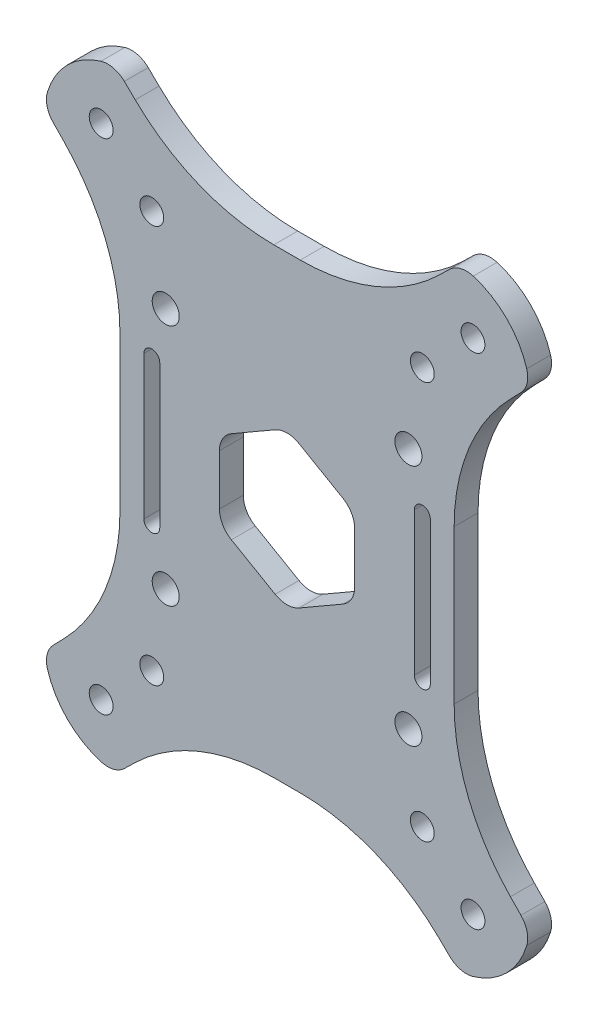
SolidWorks part; units mm, degrees
ref_plane "Draufsicht" through (0, 0, 0) normal (0, 0, 1) x (1, 0, 0)
ref_plane "Seitenansicht" through (0, 0, 0) normal (0, 1, 0) x (1, 0, 0)
ref_plane "Vorderansicht" through (0, 0, 0) normal (1, 0, 0) x (0, 0, -1)
sketch "Skizze1" plane through (0, 0, 0) normal (0, 0, 1) x (1, 0, 0)
  line L0 (-15.25, 15.25) -> (15.25, -15.25) construction
  line L1 (-15.25, 15.25) -> (15.25, 15.25) construction
  line L2 (-15.25, 15.25) -> (-15.25, -15.25) construction
  line L3 (-15.25, -15.25) -> (15.25, -15.25) construction
  line L4 (15.25, 15.25) -> (15.25, -15.25) construction
  line L5 (-17, 25) -> (17, 25) construction
  line L6 (-17, 25) -> (-17, -25) construction
  line L7 (-17, -25) -> (17, -25) construction
  line L9 (15.25, 15.25) -> (-15.25, -15.25) construction
  line L10 (-17, 25) -> (17, -25) construction
  line L11 (17, -25) -> (17, 25) construction
  line L12 (17, 25) -> (-17, -25) construction
  line L13 (17, 25) -> (23.364, 31.364) construction
  line L14 (-23.364, 31.364) -> (-17, 25) construction
  line L16 (-23.364, -31.364) -> (-17, -25) construction
  line L18 (23.364, -31.364) -> (17, -25) construction
  dimension "D1" = 30.5
  dimension "D2" = 30.5
  dimension "D3" = 50
  dimension "D4" = 34
  dimension "D5" = 135
  dimension "D6" = 9
sketch "Skizze2" plane through (0, 0, 0) normal (0, 0, 1) x (1, 0, 0)
  line L0 (-21, -19.8076) -> (-21, 19.8076)
  line L1 (-21, 19.8076) -> (-30.4824, 29.5654)
  line L2 (-30.4824, 29.5654) -> (-21.5654, 38.4824) construction
  line L3 (-21.5654, 38.4824) -> (-11.8076, 29)
  line L4 (-11.8076, 29) -> (11.8076, 29)
  line L5 (11.8076, 29) -> (21.5654, 38.4824)
  line L6 (21.5654, 38.4824) -> (30.4824, 29.5654) construction
  line L7 (30.4824, 29.5654) -> (21, 19.8076)
  line L8 (21, 19.8076) -> (21, -19.8076)
  line L9 (21, -19.8076) -> (30.4824, -29.5654)
  line L10 (30.4824, -29.5654) -> (21.5654, -38.4824) construction
  line L11 (21.5654, -38.4824) -> (11.8076, -29)
  line L12 (11.8076, -29) -> (-11.8076, -29)
  line L13 (-11.8076, -29) -> (-21.5654, -38.4824)
  line L14 (-21.5654, -38.4824) -> (-30.4824, -29.5654) construction
  line L15 (-30.4824, -29.5654) -> (-21, -19.8076)
  line L16 (-23.364, 31.364) -> (-17, 25) construction
  line L17 (21, -19.8076) -> (-21, 19.8076) construction
  line L18 (-21, -19.8076) -> (21, 19.8076) construction
  line L19 (-21, 19.8076) -> (-11.8076, 29) construction
  line L20 (-26.0239, 34.0239) -> (-20.5355, 28.5355) construction
  line L21 (11.8076, 29) -> (21, 19.8076) construction
  line L22 (21, -19.8076) -> (11.8076, -29) construction
  line L23 (-11.8076, -29) -> (-21, -19.8076) construction
  arc A0 (-21.5654, 38.4824) -> (-30.4824, 29.5654) centre (-20.5355, 28.5355) ccw
  arc A1 (21.5654, 38.4824) -> (30.4824, 29.5654) centre (20.5355, 28.5355) cw
  arc A2 (30.4824, -29.5654) -> (21.5654, -38.4824) centre (20.5355, -28.5355) cw
  arc A3 (-30.4824, -29.5654) -> (-21.5654, -38.4824) centre (-20.5355, -28.5355) ccw
  point P18 (-16.4038, 24.4038)
  dimension "D3" = 6
  dimension "D4" = 10
  dimension "D1" = 42
  dimension "D2" = 0.82
  dimension "D5" = 13
extrude "Aufsatz-Linear austragen1" add sketch "Skizze2" along normal blind 3
fillet "Verrundung1" radius 25 8 edges at (-11.8076, -29, 1.5) (11.8076, -29, 1.5) (-21, -19.8076, 1.5) (-21, 19.8076, 1.5) (-11.8076, 29, 1.5) (11.8076, 29, 1.5) (21, 19.8076, 1.5) (21, -19.8076, 1.5)
fillet "Verrundung2" radius 3 8 edges at (-30.4824, 29.5654, 1.5) (-30.4824, -29.5654, 1.5) (-21.5654, 38.4824, 1.5) (21.5654, 38.4824, 1.5) (30.4824, 29.5654, 1.5) (30.4824, -29.5654, 1.5) (21.5654, -38.4824, 1.5) (-21.5654, -38.4824, 1.5)
sketch "Skizze3" plane through (0, 0, 0) normal (0, 0, -1) x (-1, 0, 0)
  line L0 (17, 25) -> (-17, -25) construction
  circle A0 centre (0, 0) radius 8.5
  dimension "D1" = 17
extrude "Schnitt-Linear austragen1" cut sketch "Skizze3" against normal through all
sketch "Skizze7" plane through (0, 0, 3) normal (0, 0, 1) x (1, 0, 0)
  line L0 (-15.25, 15.25) -> (15.25, -15.25) construction
  line L1 (-1.5, 8.9489) -> (-7, 5.7735)
  line L2 (-8.5, 3.1754) -> (-8.5, -3.1754)
  line L3 (-7, -5.7735) -> (-1.5, -8.9489)
  line L4 (1.5, -8.9489) -> (7, -5.7735)
  line L5 (8.5, -3.1754) -> (8.5, 3.1754)
  line L6 (7, 5.7735) -> (1.5, 8.9489)
  circle A0 centre (0, 0) radius 8.5 construction
  circle A1 centre (0, 0) radius 8.5 construction
  arc A2 (-7, 5.7735) -> (-8.5, 3.1754) centre (-5.5, 3.1754) ccw
  arc A3 (-8.5, -3.1754) -> (-7, -5.7735) centre (-5.5, -3.1754) ccw
  arc A4 (-1.5, -8.9489) -> (1.5, -8.9489) centre (0, -6.3509) ccw
  arc A5 (7, -5.7735) -> (8.5, -3.1754) centre (5.5, -3.1754) ccw
  arc A6 (8.5, 3.1754) -> (7, 5.7735) centre (5.5, 3.1754) ccw
  arc A7 (-1.5, 8.9489) -> (1.5, 8.9489) centre (0, 6.3509) cw
  dimension "D1" = 3
extrude "Schnitt-Linear austragen4" cut sketch "Skizze7" against normal blind 4
sketch "Skizze4" plane through (0, 0, 0) normal (0, 0, -1) x (-1, 0, 0)
  circle A0 centre (-23.364, 31.364) radius 1.5
  circle A1 centre (-17, 25) radius 1.5
  circle A2 centre (-15.25, 15.25) radius 1.7
  circle A3 centre (-17, -25) radius 1.5
  circle A4 centre (-15.25, -15.25) radius 1.7
  circle A5 centre (-23.364, -31.364) radius 1.5
  circle A6 centre (23.364, -31.364) radius 1.5
  circle A7 centre (17, -25) radius 1.5
  circle A8 centre (15.25, -15.25) radius 1.7
  circle A9 centre (23.364, 31.364) radius 1.5
  circle A10 centre (17, 25) radius 1.5
  circle A11 centre (15.25, 15.25) radius 1.7
  dimension "D1" = 3
  dimension "D2" = 3.4
extrude "Schnitt-Linear austragen2" cut sketch "Skizze4" against normal through all
sketch "Skizze5" plane through (0, 0, 3) normal (0, 0, 1) x (1, 0, 0)
  line L0 (17, 9) -> (17, -9) construction
  line L1 (18, 9) -> (18, -9)
  line L2 (16, 9) -> (16, -9)
  line L3 (-17, 9) -> (-17, -9) construction
  line L4 (-16, 9) -> (-16, -9)
  line L5 (-18, 9) -> (-18, -9)
  line L6 (17, 0) -> (-17, 0) construction
  arc A0 (18, 9) -> (16, 9) centre (17, 9) ccw
  arc A1 (16, -9) -> (18, -9) centre (17, -9) ccw
  arc A2 (-16, 9) -> (-18, 9) centre (-17, 9) ccw
  arc A3 (-18, -9) -> (-16, -9) centre (-17, -9) ccw
  point P2 (17, 0)
  point P7 (-17, 0)
  dimension "D1" = 2
  dimension "D2" = 18
  dimension "D3" = 34
extrude "Schnitt-Linear austragen3" cut sketch "Skizze5" against normal through all
equation "\"Oberflaeche_cm\"= \"SW-Oberfläche\" / 100"
